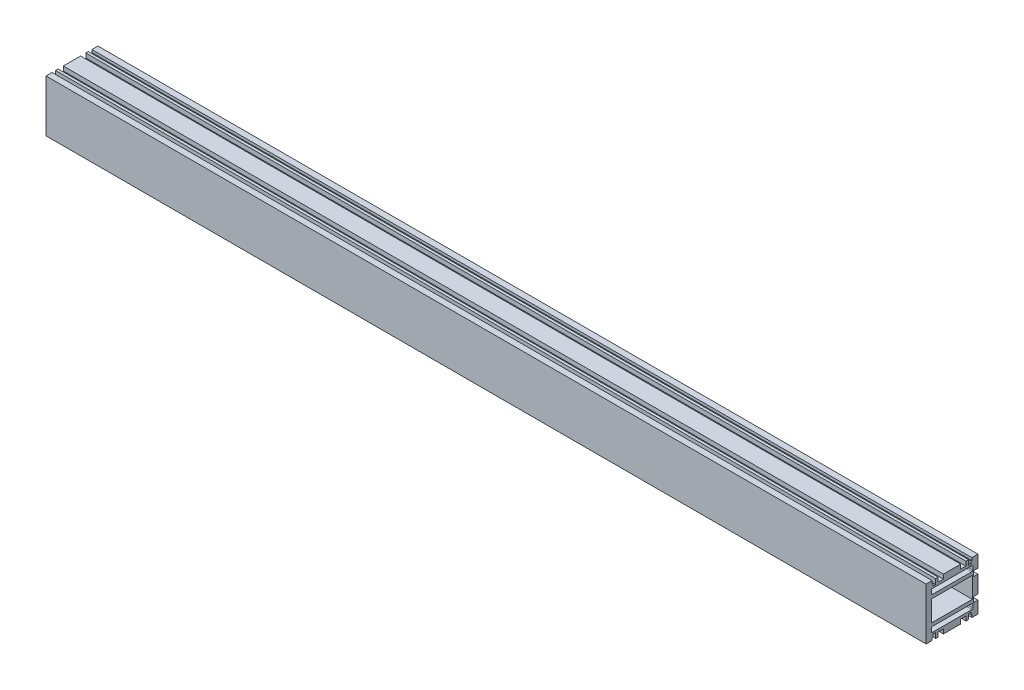
SolidWorks part; units mm, degrees
ref_plane "前视基准面" through (0, 0, 0) normal (0, 0, 1) x (1, 0, 0)
ref_plane "上视基准面" through (0, 0, 0) normal (0, 1, 0) x (1, 0, 0)
ref_plane "右视基准面" through (0, 0, 0) normal (1, 0, 0) x (0, 0, -1)
sketch "草图1" plane through (0, 0, 0) normal (1, 0, 0) x (0, 0, -1)
  line L0 (-15, 15) -> (15, -15) construction
  line L1 (-15, 15) -> (-11.5, 15)
  line L2 (-15, 15) -> (-15, -15)
  line L3 (-15, -15) -> (-11.5, -15)
  line L4 (15, 15) -> (15, 8)
  line L5 (15, 15) -> (-15, -15) construction
  line L6 (-11.5, 15) -> (-11.5, 13.5)
  line L7 (-11.5, 13.5) -> (-11, 13.5)
  line L8 (-11, 13.5) -> (-11, 12)
  line L9 (-11, 12) -> (-9.5, 12)
  line L10 (-9.5, 12) -> (-9.5, 15)
  line L11 (-9.5, 15) -> (-8, 15)
  line L12 (-8, 15) -> (-8, 12.5)
  line L13 (-8, 12.5) -> (-5, 12.5)
  line L14 (-5, 12.5) -> (-5, 15)
  line L15 (-5, 15) -> (5, 15)
  line L16 (0, 21.5201) -> (0, -18.309) construction
  line L17 (0, 55) -> (0, -55) construction
  line L18 (5, 12.5) -> (5, 15)
  line L19 (8, 12.5) -> (5, 12.5)
  line L20 (8, 15) -> (8, 12.5)
  line L21 (9.5, 15) -> (8, 15)
  line L22 (9.5, 12) -> (9.5, 15)
  line L23 (11, 12) -> (9.5, 12)
  line L24 (11, 13.5) -> (11, 12)
  line L25 (11.5, 13.5) -> (11, 13.5)
  line L26 (11.5, 15) -> (11.5, 13.5)
  line L27 (8, 15) -> (9.5, 15)
  line L28 (11.5, 15) -> (15, 15)
  line L29 (-19.8303, 0) -> (22.13, 0) construction
  line L30 (55, 0) -> (-55, 0) construction
  line L31 (8, -15) -> (9.5, -15)
  line L32 (11.5, -15) -> (11.5, -13.5)
  line L33 (11.5, -13.5) -> (11, -13.5)
  line L34 (11, -13.5) -> (11, -12)
  line L35 (11, -12) -> (9.5, -12)
  line L36 (9.5, -12) -> (9.5, -15)
  line L37 (9.5, -15) -> (8, -15)
  line L38 (8, -15) -> (8, -12.5)
  line L39 (8, -12.5) -> (5, -12.5)
  line L40 (5, -12.5) -> (5, -15)
  line L41 (-5, -15) -> (5, -15)
  line L42 (-5, -12.5) -> (-5, -15)
  line L43 (-8, -12.5) -> (-5, -12.5)
  line L44 (-8, -15) -> (-8, -12.5)
  line L45 (-9.5, -15) -> (-8, -15)
  line L46 (-9.5, -12) -> (-9.5, -15)
  line L47 (-11, -12) -> (-9.5, -12)
  line L48 (-11, -13.5) -> (-11, -12)
  line L49 (-11.5, -13.5) -> (-11, -13.5)
  line L50 (-11.5, -15) -> (-11.5, -13.5)
  line L51 (-9.5, -15) -> (-8, -15)
  line L52 (-5, -15) -> (5, -15)
  line L53 (8, -15) -> (9.5, -15)
  line L54 (11.5, -15) -> (15, -15)
  line L55 (15, 8) -> (12.5, 8)
  line L56 (12.5, 8) -> (12.5, 5)
  line L57 (12.5, 5) -> (15, 5)
  line L58 (12.5, -5) -> (15, -5)
  line L59 (12.5, -8) -> (12.5, -5)
  line L60 (15, -8) -> (12.5, -8)
  line L61 (15, 5) -> (15, -5)
  line L62 (15, -8) -> (15, -15)
  line L63 (12, -10.5) -> (12, -8.5)
  line L64 (-11.5, 11) -> (11.5, 11)
  line L65 (-12, 10.5) -> (-12, 8.5)
  line L66 (-11.5, 8) -> (11.5, 8)
  line L67 (12, 10.5) -> (12, 8.5)
  line L68 (-11.5, -8) -> (11.5, -8)
  line L69 (-12, -10.5) -> (-12, -8.5)
  line L70 (-11.5, -11) -> (11.5, -11)
  line L72 (-11.75, 6) -> (11.75, 6)
  line L73 (-11.75, 6) -> (-11.75, -6)
  line L74 (-11.75, -6) -> (11.75, -6)
  line L75 (11.75, 6) -> (11.75, -6)
  arc A0 (12, 8.5) -> (11.5, 8) centre (11.5, 8.5) cw
  arc A1 (11.5, 11) -> (12, 10.5) centre (11.5, 10.5) cw
  arc A2 (-11.5, 11) -> (-12, 10.5) centre (-11.5, 10.5) ccw
  arc A3 (-11.5, 8) -> (-12, 8.5) centre (-11.5, 8.5) cw
  arc A8 (-11.5, -8) -> (-12, -8.5) centre (-11.5, -8.5) ccw
  arc A9 (-11.5, -11) -> (-12, -10.5) centre (-11.5, -10.5) cw
  arc A10 (11.5, -11) -> (12, -10.5) centre (11.5, -10.5) ccw
  arc A11 (12, -8.5) -> (11.5, -8) centre (11.5, -8.5) ccw
  point P69 (12, 11)
  point P72 (-12, 11)
  point P77 (-11, -13.5)
  point P80 (11, -13.5)
  point P83 (11, 13.5)
  point P86 (-11, 13.5)
  point P99 (-12, -11)
  point P100 (12, -11)
  dimension "D17" = 0.5
  dimension "D1" = 3.5
  dimension "D2" = 1.5
  dimension "D3" = 0.5
  dimension "D4" = 1.5
  dimension "D5" = 3
  dimension "D6" = 30
  dimension "D7" = 30
  dimension "D8" = 1.5
  dimension "D9" = 2.5
  dimension "D10" = 3
  dimension "D11" = 2.5
  dimension "D12" = 7
  dimension "D13" = 3
  dimension "D14" = 4
  dimension "D15" = 3
  dimension "D16" = 24
  dimension "D19" = 23.5
  dimension "D20" = 12
extrude "凸台-拉伸1" add sketch "草图1" along normal mid plane 509
hole_wizard "M6 螺纹孔1" positions "草图3" profile "草图2" tap size "M6" standard "GB"
sketch "草图3" plane through (0, 0, -15) normal (0, 0, -1) x (-1, 0, 0)
  point P0 (16.5, 0)
  point P3 (1.5, 0)
  point P6 (-219.5, 0)
  point P9 (-234.5, 0)
sketch "草图2" plane through (-16.5, 0, -15) normal (1, 0, 0) x (0, 1, 0)
  line L0 (0, 0) -> (0, 20.5022)
  line L1 (0, 20.5022) -> (2.5, 19)
  line L2 (2.5, 19) -> (2.5, 0)
  line L5 (2.5, 0) -> (0, 0)
  line L10 (0, 20.5022) -> (-2.5, 19) construction
  line L11 (0, -6.35) -> (0, 107.95) construction
  dimension "螺纹孔钻头直径" = 5
  dimension "螺纹孔钻头深度" = 19
  dimension "导头角度" = 118
cosmetic thread "孔螺蚊线1" parameters "D1"=3.25, "D2"=6
cosmetic thread "孔螺蚊线2" parameters "D1"=3.25, "D2"=6
cosmetic thread "孔螺蚊线3" parameters "D1"=3.25, "D2"=6
cosmetic thread "孔螺蚊线4" parameters "D1"=3.25, "D2"=6
hole_wizard "M6 螺纹孔2" positions "草图5" profile "草图4" tap size "M6" standard "GB"
sketch "草图5" plane through (0, -15, 0) normal (0, -1, 0) x (-1, 0, 0)
  point P0 (-219.5, 0)
  point P3 (-234.5, 0)
  point P6 (234.5, 0)
  point P9 (219.5, 0)
sketch "草图4" plane through (219.5, -15, 0) normal (1, 0, 0) x (0, 0, -1)
  line L0 (0, 0) -> (0, 20.5022)
  line L1 (0, 20.5022) -> (2.5, 19)
  line L2 (2.5, 19) -> (2.5, 0)
  line L5 (2.5, 0) -> (0, 0)
  line L10 (0, 20.5022) -> (-2.5, 19) construction
  line L11 (0, -6.35) -> (0, 107.95) construction
  dimension "螺纹孔钻头直径" = 5
  dimension "螺纹孔钻头深度" = 19
  dimension "导头角度" = 118
cosmetic thread "孔螺蚊线5" parameters "D1"=9, "D2"=6
cosmetic thread "孔螺蚊线6" parameters "D1"=9, "D2"=6
cosmetic thread "孔螺蚊线7" parameters "D1"=9, "D2"=6
cosmetic thread "孔螺蚊线8" parameters "D1"=9, "D2"=6
hole_wizard "M4 螺纹孔1" positions "草图7" profile "草图6" tap size "M4" standard "GB"
sketch "草图7" plane through (0, -15, 0) normal (0, -1, 0) x (-1, 0, 0)
  line L0 (-254.5, 15) -> (254.5, 15) construction
  line L1 (-254.5, -5) -> (-254.5, 5) construction
  point P0 (-131, 0)
  point P2 (51.5, 0)
  dimension "D1" = 15
  dimension "D2" = 15
  dimension "D3" = 123.5
  dimension "D4" = 306
sketch "草图6" plane through (131, -15, 0) normal (1, 0, 0) x (0, 0, -1)
  line L0 (0, 0) -> (0, 12.4914)
  line L1 (0, 12.4914) -> (1.65, 11.5)
  line L2 (1.65, 11.5) -> (1.65, 0)
  line L5 (1.65, 0) -> (0, 0)
  line L10 (0, 12.4914) -> (-1.65, 11.5) construction
  line L11 (0, -6.35) -> (0, 107.95) construction
  dimension "螺纹孔钻头直径" = 3.3
  dimension "螺纹孔钻头深度" = 11.5
  dimension "导头角度" = 118
cosmetic thread "孔螺蚊线9" parameters "D1"=8, "D2"=4
cosmetic thread "孔螺蚊线10" parameters "D1"=8, "D2"=4
